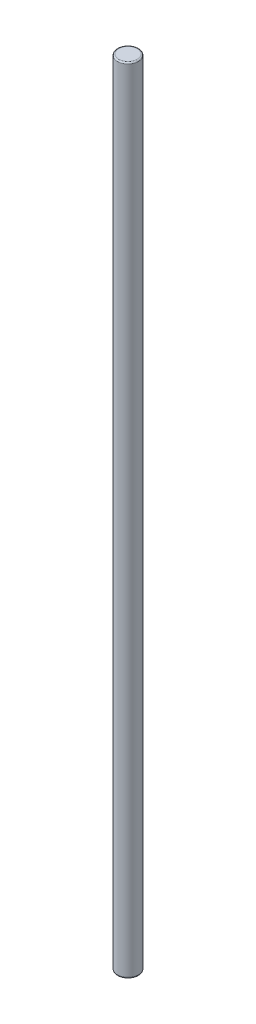
SolidWorks part; units mm, degrees
ref_plane "Front Plane" through (0, 0, 0) normal (0, 0, 1) x (1, 0, 0)
ref_plane "Top Plane" through (0, 0, 0) normal (0, 1, 0) x (1, 0, 0)
ref_plane "Right Plane" through (0, 0, 0) normal (1, 0, 0) x (0, 0, -1)
sketch "Sketch1" plane through (0, 0, 0) normal (0, 1, 0) x (1, 0, 0)
  circle A0 centre (0, 0) radius 4
  dimension "D1" = 8
extrude "Boss-Extrude1" add sketch "Sketch1" along normal blind 300
fillet "Fillet1" radius 0.5 2 edges at (0, 300, 4) (0, 0, 4)
